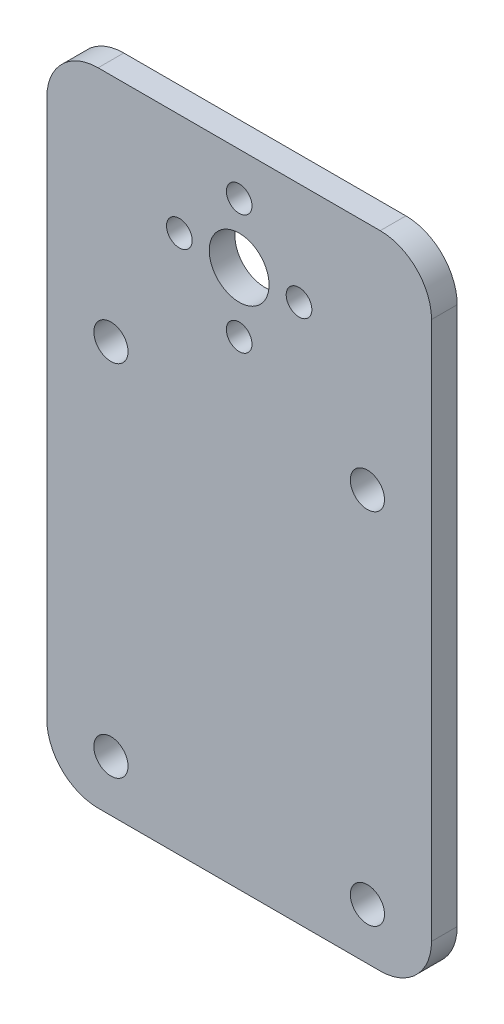
SolidWorks part; units mm, degrees
material "AISI 1020 钢，冷轧"
ref_plane "前视基准面" through (0, 0, 0) normal (0, 0, 1) x (1, 0, 0)
ref_plane "上视基准面" through (0, 0, 0) normal (0, 1, 0) x (1, 0, 0)
ref_plane "右视基准面" through (0, 0, 0) normal (1, 0, 0) x (0, 0, -1)
other "Configuration Table"
sketch "草图1" plane through (0, 0, 0) normal (0, 0, 1) x (1, 0, 0)
  line L0 (0, 32.5) -> (0, 18.5) construction
  line L1 (-22.5, -37.5) -> (22.5, -37.5)
  line L2 (-22.5, -37.5) -> (-22.5, 37.5)
  line L3 (-22.5, 37.5) -> (22.5, 37.5)
  line L4 (22.5, -37.5) -> (22.5, 37.5)
  line L5 (-22.5, -37.5) -> (22.5, 37.5) construction
  line L6 (-22.5, 37.5) -> (22.5, -37.5) construction
  line L7 (-15, 10.5) -> (15, 10.5) construction
  line L8 (-15, 10.5) -> (-15, -31.5) construction
  line L9 (-15, -31.5) -> (15, -31.5) construction
  line L10 (15, 10.5) -> (15, -31.5) construction
  line L11 (-7, 25.5) -> (7, 25.5) construction
  circle A4 centre (-15, 10.5) radius 2
  circle A5 centre (15, 10.5) radius 2
  circle A6 centre (15, -31.5) radius 2
  circle A7 centre (-15, -31.5) radius 2
  circle A8 centre (0, 32.5) radius 1.5
  circle A9 centre (7, 25.5) radius 1.5
  circle A10 centre (0, 18.5) radius 1.5
  circle A11 centre (-7, 25.5) radius 1.5
  circle A12 centre (0, 25.5) radius 3.5
  point P0 (0, 0)
  point P6 (0, 0)
  point P19 (0, 25.5)
  point P20 (0, 25.5)
  dimension "D3" = 4
  dimension "D4" = 30
  dimension "D5" = 42
  dimension "D6" = 6
  dimension "D9" = 3
  dimension "D11" = 7
  dimension "D1" = 45
  dimension "D2" = 75
  dimension "D7" = 14
  dimension "D8" = 14
  dimension "D10" = 8
extrude "凸台-拉伸1" add sketch "草图1" along normal blind 3
fillet "圆角1" radius 6 4 edges at (22.5, -37.5, 1.5) (-22.5, -37.5, 1.5) (22.5, 37.5, 1.5) (-22.5, 37.5, 1.5)
